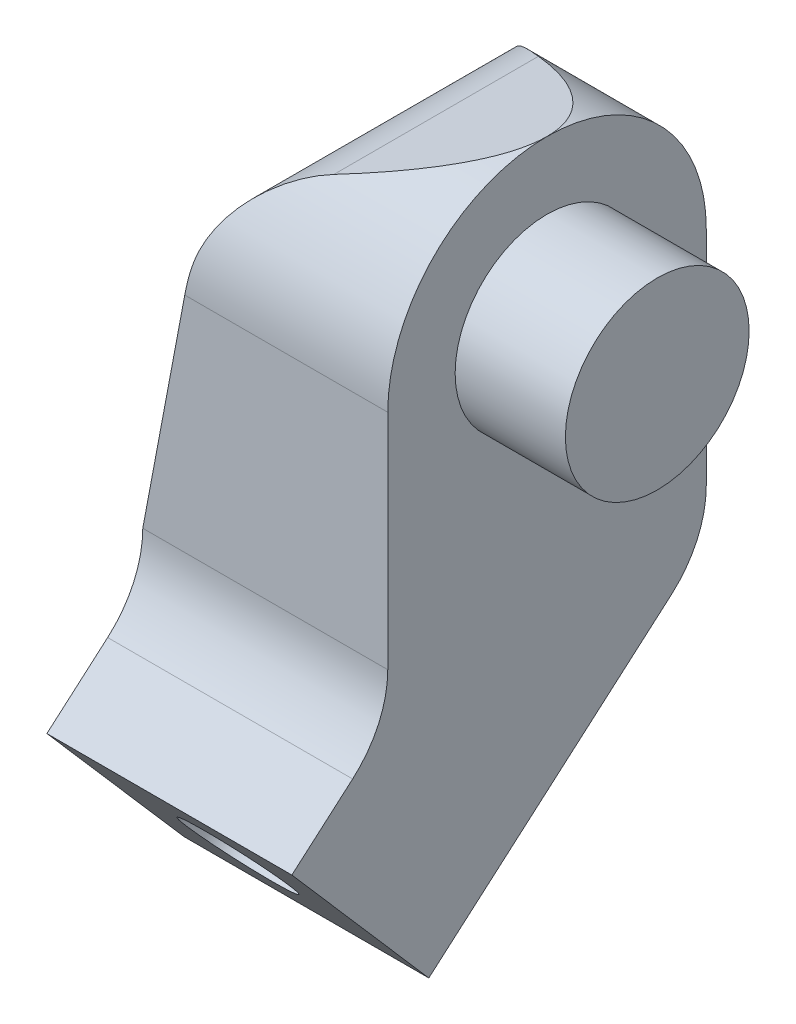
SolidWorks part; units mm, degrees
ref_plane "Alzado" through (0, 0, 0) normal (0, 0, 1) x (1, 0, 0)
ref_plane "Planta" through (0, 0, 0) normal (0, 1, 0) x (1, 0, 0)
ref_plane "Vista lateral" through (0, 0, 0) normal (1, 0, 0) x (0, 0, -1)
sketch "Croquis3" plane through (0, 0, 0) normal (1, 0, 0) x (0, 0, -1)
  line L0 (10.1489, 8.6018) -> (10.1489, -2.3183)
  line L1 (8.4277, -6.0932) -> (-3.4406, -16.4018)
  line L2 (-3.4406, -16.4018) -> (-10.1489, -8.6786)
  line L3 (-5.4511, 8.6018) -> (-5.4511, -2.3183)
  line L4 (-7.1723, -6.0932) -> (-10.1489, -8.6786)
  arc A0 (10.1489, 8.6018) -> (-5.4511, 8.6018) centre (2.3489, 8.6018) ccw
  arc A1 (10.1489, -2.3183) -> (8.4277, -6.0932) centre (5.1489, -2.3183) cw
  arc A2 (-5.4511, -2.3183) -> (-7.1723, -6.0932) centre (-10.4511, -2.3183) cw
  dimension "D1" = 15.6
  dimension "D2" = 5
  dimension "D3" = 5
extrude "Saliente-Extruir1" add sketch "Croquis3" along normal mid plane 12
sketch "Croquis4" plane through (0, 0, 0) normal (0, 0, 1) x (1, 0, 0)
  line L0 (6, 16.4018) -> (-6, 16.4018)
  line L1 (-6, 16.4018) -> (-6, -2.3183)
  line L2 (-6, -2.3183) -> (-3.7519, 9.6213)
  line L3 (0.5699, 14.5815) -> (6, 16.4018)
  arc A0 (-3.7519, 9.6213) -> (0.5699, 14.5815) centre (2.6359, 8.4186) cw
  dimension "D1" = 6.5
  dimension "D2" = 5.7271
  dimension "D3" = 12.1495
extrude "Cortar-Extruir1" cut sketch "Croquis4" against normal through all both and the other way through all
sketch "Croquis5" plane through (6, 0, 0) normal (1, 0, 0) x (0, 0, -1)
  line L0 (-5.4511, 8.6018) -> (-5.4511, -2.3183) construction
  circle A0 centre (2.3489, 8.6018) radius 4.5
  dimension "D1" = 9
  dimension "D2" = 7.8
  dimension "D3" = 7.8
extrude "Saliente-Extruir2" add sketch "Croquis5" along normal blind 5.4
sketch "Croquis6" plane through (0, -8.7564, 10.0813) normal (0, -0.6558, 0.755) x (1, 0, 0)
  line L0 (6, 0.1031) -> (-6, 0.1031) construction
  line L1 (6, 0.1031) -> (6, -10.1267) construction
  circle A0 centre (0, -5.0169) radius 2.5
  dimension "D1" = 5
  dimension "D2" = 5.12
  dimension "D3" = 6
extrude "Cortar-Extruir2" cut sketch "Croquis6" against normal blind 5.4 and the other way through all
